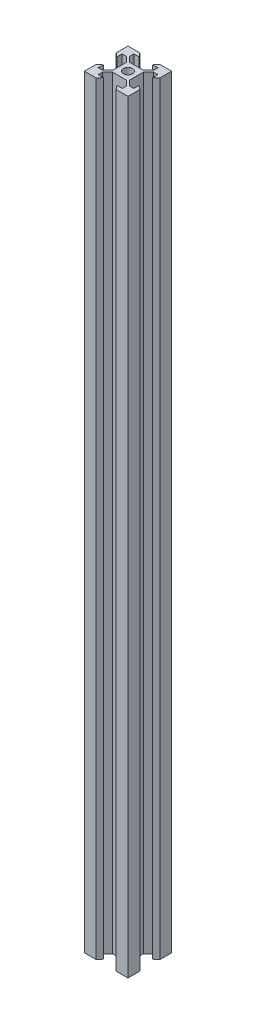
SolidWorks part; units mm, degrees
ref_plane "Front Plane" through (0, 0, 0) normal (0, 0, 1) x (1, 0, 0)
ref_plane "Top Plane" through (0, 0, 0) normal (0, 1, 0) x (1, 0, 0)
ref_plane "Right Plane" through (0, 0, 0) normal (1, 0, 0) x (0, 0, -1)
sketch "Sketch1" plane through (0, 0, 0) normal (0, 1, 0) x (1, 0, 0)
  line L0 (0, 0) -> (5.42, 0)
  line L2 (20, 20) -> (14.58, 20)
  line L3 (0, 20) -> (0, 14.58)
  line L5 (0, 5.415) -> (1.8, 6.875)
  line L6 (15.5, 18.2) -> (13.125, 18.2)
  line L7 (6.1, 6.85) -> (6.1, 13.15)
  line L8 (1.8, 15.5) -> (1.8, 13.12)
  line L10 (4.5, 1.8) -> (6.875, 1.8)
  line L12 (18.2, 4.5) -> (18.2, 5.415)
  line L17 (13.1475, 1.8) -> (15.5, 1.8)
  line L18 (13.9, 13.15) -> (13.9, 6.85)
  line L21 (13.15, 13.9) -> (6.85, 13.9)
  line L23 (6.85, 6.1) -> (13.15, 6.1)
  line L25 (6.875, 18.2) -> (4.5, 18.2)
  line L26 (0, 5.415) -> (0, 0)
  line L27 (6.1, 13.15) -> (3.75, 15.5)
  line L28 (6.85, 13.9) -> (4.5, 16.25)
  line L29 (13.15, 13.9) -> (15.5, 16.25)
  line L30 (15.5, 18.2) -> (13.125, 18.2)
  line L31 (4.5, 3.75) -> (6.85, 6.1)
  line L32 (6.1, 6.85) -> (3.75, 4.5)
  line L33 (0, 14.58) -> (0, 14.7)
  line L35 (18.2, 13.12) -> (18.2, 15.5)
  line L37 (16.25, 4.5) -> (13.9, 6.85)
  line L38 (15.5, 3.75) -> (13.15, 6.1)
  line L40 (5.42, 20) -> (0, 20)
  line L41 (13.9, 13.15) -> (16.25, 15.5)
  line L42 (18.2, 15.5) -> (18.2, 13.12)
  line L43 (14.58, 0) -> (20, 0)
  line L44 (14.58, 20) -> (20, 20)
  line L45 (1.8, 6.875) -> (1.8, 5.415)
  line L46 (5.42, 20) -> (6.875, 18.2)
  line L47 (13.125, 18.2) -> (14.58, 20)
  line L50 (14.58, 20) -> (20, 20)
  line L54 (5.42, 0) -> (6.875, 1.8)
  line L55 (18.2, 13.12) -> (18.2, 15.5)
  line L56 (13.1475, 1.8) -> (14.58, 0)
  line L57 (15.5, 18.2) -> (13.125, 18.2)
  line L58 (4.5, 18.2) -> (6.875, 18.2)
  line L59 (1.8, 15.5) -> (1.8, 13.12)
  line L60 (4.5, 18.2) -> (6.875, 18.2)
  line L61 (1.8, 15.5) -> (1.8, 13.12)
  line L62 (5.42, 20) -> (6.875, 18.2)
  line L63 (1.8, 13.12) -> (1.8, 14.7)
  line L64 (18.2, 5.415) -> (18.2, 4.5)
  line L65 (4.5, 18.2) -> (6.875, 18.2)
  line L69 (1.8, 13.12) -> (1.8, 13.125)
  line L70 (20, 5.415) -> (20, 0)
  line L71 (1.8, 14.7) -> (1.8, 13.12)
  line L72 (1.8, 13.12) -> (1.8, 13.125)
  line L73 (0, 5.415) -> (1.8, 6.875)
  line L74 (13.1475, 1.8) -> (15.5, 1.8)
  line L75 (14.58, 20) -> (20, 20)
  line L79 (1.8, 14.7) -> (1.8, 15.5)
  line L80 (5.42, 0) -> (6.875, 1.8)
  line L81 (15.5, 18.2) -> (13.125, 18.2)
  line L82 (1.8, 15.5) -> (1.8, 14.58)
  line L83 (18.2, 15.5) -> (18.2, 13.12)
  line L84 (15.5, 1.8) -> (13.1475, 1.8)
  line L85 (1.8, 14.58) -> (1.8, 13.125)
  line L86 (18.2, 13.12) -> (20, 14.58)
  line L87 (1.8, 13.125) -> (0, 14.58)
  line L89 (1.8, 13.125) -> (1.8, 13.12)
  line L91 (1.8, 14.58) -> (1.8, 13.12)
  line L92 (1.8, 14.58) -> (1.8, 13.12)
  line L94 (1.8, 14.58) -> (1.8, 13.12)
  line L98 (0, 20) -> (4.5, 20)
  line L99 (1.8, 5.415) -> (1.8, 4.5)
  line L100 (18.2, 6.85) -> (18.2, 6.8625)
  line L101 (18.2, 4.5) -> (18.2, 5.415)
  line L102 (18.2154, 6.8625) -> (18.2, 6.8625)
  line L108 (1.8, 13.12) -> (1.8, 13.125)
  line L110 (6.85, 13.9) -> (13.15, 13.9)
  line L111 (18.2, 6.85) -> (18.2, 6.8625)
  line L112 (4.5, 18.2) -> (4.5, 16.25)
  line L113 (18.2, 5.415) -> (18.2, 6.8625)
  line L114 (3.75, 15.5) -> (1.8, 15.5)
  line L115 (20, 5.415) -> (18.2, 6.85)
  line L116 (1.8, 15.5) -> (3.75, 15.5)
  line L117 (20, 20) -> (20, 14.58)
  line L118 (6.1, 13.15) -> (6.1, 6.85)
  line L119 (6.85, 6.1) -> (13.15, 6.1)
  line L120 (20, 14.58) -> (20, 20)
  line L121 (0, 20) -> (4.5, 20)
  line L122 (20, 20) -> (15.5, 20)
  line L125 (15.5, 18.2) -> (15.5, 16.25)
  line L128 (20, 0) -> (20, 4.5)
  line L131 (1.8, 5.415) -> (1.8, 4.5)
  line L132 (6.875, 1.8) -> (4.5, 1.8)
  line L133 (4.5, 1.8) -> (6.875, 1.8)
  line L134 (18.2, 4.5) -> (16.25, 4.5)
  line L135 (15.5, 3.75) -> (15.5, 1.8)
  line L136 (6.875, 1.8) -> (4.5, 1.8)
  line L137 (0, 0) -> (4.5, 0)
  line L138 (4.5, 1.8) -> (4.5, 3.75)
  line L139 (3.75, 4.5) -> (1.8, 4.5)
  line L140 (16.25, 15.5) -> (18.2, 15.5)
  circle A0 centre (10, 10) radius 2.1
extrude "Boss-Extrude1" add sketch "Sketch1" along normal blind 350 contours L41 L140 L35 L86 L117 L2 L75 L47 L6 L125 L29 L21 L28 L112 L25 L46 L40 L3 L87 L71 L61 L8 L114 L27 L7 L32 L139 L99 L45 L5 L26 L0 L54 L10 L138 L31 L23 L38 L135 L17 L56 L43 L70 L115 L113 L12 L134
